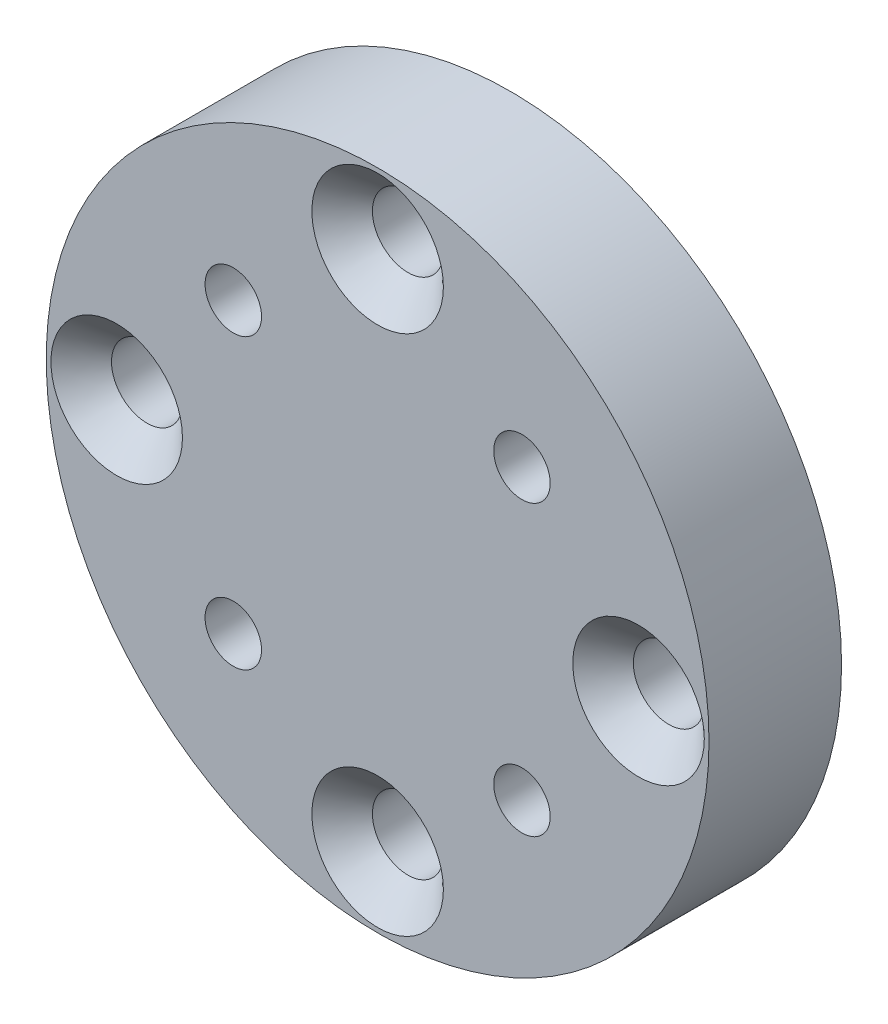
SolidWorks part; units mm, degrees
material "6061 Alloy"
ref_plane "Front Plane" through (0, 0, 0) normal (0, 0, 1) x (1, 0, 0)
ref_plane "Top Plane" through (0, 0, 0) normal (0, 1, 0) x (1, 0, 0)
ref_plane "Right Plane" through (0, 0, 0) normal (1, 0, 0) x (0, 0, -1)
sketch "Sketch1" plane through (0, 0, 0) normal (0, 0, 1) x (1, 0, 0)
  circle A0 centre (0, 0) radius 15.875
  dimension "D1" = 31.75
extrude "Boss-Extrude1" add sketch "Sketch1" along normal blind 6.35
hole_wizard "CSK for M3 Flat Head Machine Screw1" positions "Sketch3" profile "Sketch4" countersink size "M3" standard "ANSI Metric" end condition through all
sketch "Sketch3" plane through (0, 0, 6.35) normal (0, 0, 1) x (1, 0, 0)
  line L0 (-12.5, 0) -> (12.5, 0) construction
  line L3 (0, 12.5) -> (0, -12.5) construction
  point P0 (0, 12.5)
  point P2 (0, -12.5)
  point P4 (12.5, 0)
  point P6 (-12.5, 0)
  dimension "D1" = 25
sketch "Sketch4" plane through (0, 12.5, 6.35) normal (1, 0, 0) x (0, -1, 0)
  line L0 (0, 0) -> (0, 6.35)
  line L1 (0, 6.35) -> (1.7, 6.35)
  line L2 (1.7, 6.35) -> (1.7, 1.45)
  line L3 (1.7, 1.45) -> (3.15, 0)
  line L5 (3.15, 0) -> (0, 0)
  line L6 (-1.7, 1.45) -> (-3.15, 0) construction
  line L11 (0, -6.35) -> (0, 107.95) construction
  dimension "Thru Hole Dia." = 3.4
  dimension "Thru Hole Depth" = 6.35
  dimension "Near C'Sink Dia." = 6.3
  dimension "Near C'Sink Angle" = 90
hole_wizard "#6-32 Tapped Hole1" positions "Sketch6" profile "Sketch5" tap size "#6-32" standard "ANSI Inch" end condition through all
sketch "Sketch6" plane through (0, 0, 6.35) normal (0, 0, 1) x (1, 0, 0)
  line L0 (-6.9148, 6.9148) -> (6.9148, -6.9148) construction
  line L3 (6.9148, 6.9148) -> (-6.9148, -6.9148) construction
  point P0 (6.9148, 6.9148)
  point P2 (6.9148, -6.9148)
  point P4 (-6.9148, -6.9148)
  point P6 (-6.9148, 6.9148)
  dimension "D1" = 19.558
sketch "Sketch5" plane through (6.9148, 6.9148, 6.35) normal (1, 0, 0) x (0, -1, 0)
  line L0 (0, 0) -> (0, 6.35)
  line L1 (0, 6.35) -> (1.3525, 6.35)
  line L2 (1.3525, 6.35) -> (1.3525, 0)
  line L5 (1.3525, 0) -> (0, 0)
  line L11 (0, -6.35) -> (0, 107.95) construction
  dimension "Thread Major Dia." = 2.7051
  dimension "Thru Tap Drill Depth" = 6.35
